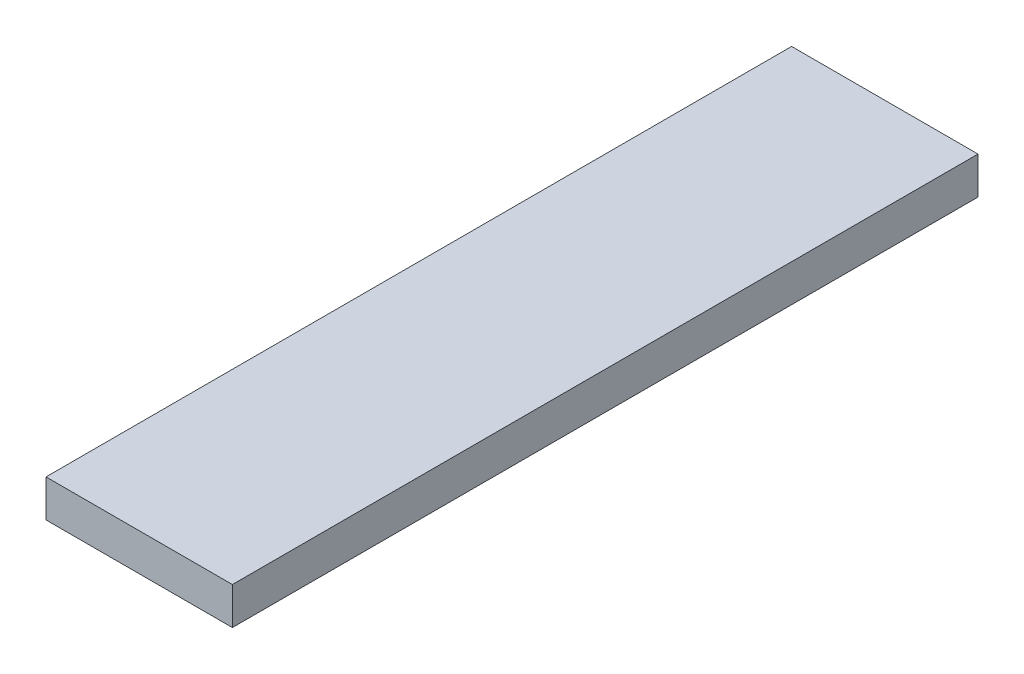
SolidWorks part; units mm, degrees
ref_plane "Front Plane" through (0, 0, 0) normal (0, 0, 1) x (1, 0, 0)
ref_plane "Top Plane" through (0, 0, 0) normal (0, 1, 0) x (1, 0, 0)
ref_plane "Right Plane" through (0, 0, 0) normal (1, 0, 0) x (0, 0, -1)
sketch "Sketch1" plane through (0, 0, 0) normal (0, 1, 0) x (1, 0, 0)
  line L1 (-5, 20) -> (5, 20)
  line L2 (-5, 20) -> (-5, -20)
  line L3 (-5, -20) -> (5, -20)
  line L4 (5, 20) -> (5, -20)
  line L5 (-5, 20) -> (5, -20) construction
  line L6 (-5, -20) -> (5, 20) construction
  point P0 (0, 0)
  dimension "D1" = 40
  dimension "D2" = 10
extrude "Boss-Extrude1" add sketch "Sketch1" along normal blind 2
